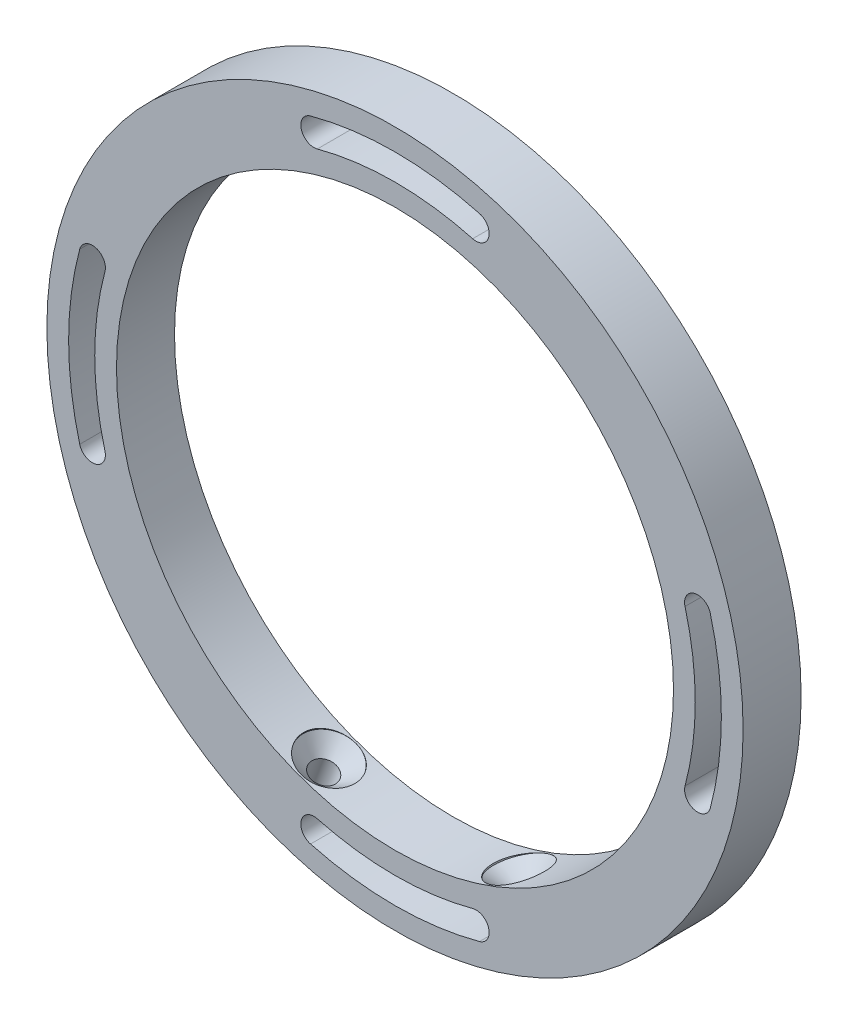
SolidWorks part; units mm, degrees
ref_plane "Piano frontale" through (0, 0, 0) normal (0, 0, 1) x (1, 0, 0)
ref_plane "Piano superiore" through (0, 0, 0) normal (0, 1, 0) x (1, 0, 0)
ref_plane "Piano destro" through (0, 0, 0) normal (1, 0, 0) x (0, 0, -1)
sketch "Schizzo2" plane through (0, 0, 0) normal (0, 0, 1) x (1, 0, 0)
  line L0 (0, -60) -> (0, 60) construction
  line L1 (-60, 0) -> (60, 0) construction
  line L2 (-15.5291, 57.9555) -> (0, 0) construction
  line L3 (0, 0) -> (13.9762, 52.16) construction
  line L4 (-52.16, 13.9762) -> (0, 0) construction
  line L5 (0, 0) -> (-52.16, -13.9762) construction
  line L6 (-13.9762, -52.16) -> (0, 0) construction
  line L7 (0, 0) -> (13.9762, -52.16) construction
  line L8 (52.16, -13.9762) -> (0, 0) construction
  line L9 (0, 0) -> (52.16, 13.9762) construction
  line L10 (13.3939, 49.9867) -> (14.5586, 54.3333) construction
  line L11 (-52.16, 13.9762) -> (-57.9555, 15.5291) construction
  line L12 (-52.16, -13.9762) -> (-57.9555, -15.5291) construction
  line L13 (-13.9762, -52.16) -> (-15.5291, -57.9555) construction
  line L14 (13.9762, -52.16) -> (15.5291, -57.9555) construction
  line L15 (52.16, 13.9762) -> (57.9555, 15.5291) construction
  circle A0 centre (0, 0) radius 60
  circle A1 centre (0, 0) radius 48
  arc A14 (-54.3333, 14.5586) -> (-54.3333, -14.5586) centre (0, 0) ccw
  arc A17 (-49.9867, 13.3939) -> (-49.9867, -13.3939) centre (0, 0) ccw
  arc A20 (-13.3939, -49.9867) -> (-14.5586, -54.3333) centre (-13.9762, -52.16) ccw
  arc A22 (14.5586, -54.3333) -> (13.3939, -49.9867) centre (13.9762, -52.16) ccw
  arc A23 (-54.3333, -14.5586) -> (-49.9867, -13.3939) centre (-52.16, -13.9762) ccw
  arc A24 (-49.9867, 13.3939) -> (-54.3333, 14.5586) centre (-52.16, 13.9762) ccw
  arc A25 (13.3939, 49.9867) -> (14.5586, 54.3333) centre (13.9762, 52.16) ccw
  arc A27 (54.3333, 14.5586) -> (49.9867, 13.3939) centre (52.16, 13.9762) ccw
  arc A28 (49.9867, -13.3939) -> (54.3333, -14.5586) centre (52.16, -13.9762) ccw
  arc A29 (-51.5325, 16.137) -> (-51.5325, -16.137) centre (0, 0) ccw construction
  arc A30 (14.5586, 54.3333) -> (-14.5586, 54.3333) centre (0, 0) ccw
  arc A31 (16.137, 51.5325) -> (-39.7413, 36.56) centre (0, 0) ccw construction
  arc A32 (13.3939, 49.9867) -> (-13.3939, 49.9867) centre (0, 0) ccw
  arc A33 (49.9867, -13.3939) -> (49.9867, 13.3939) centre (0, 0) ccw
  arc A34 (51.5325, -16.137) -> (51.5325, 16.137) centre (0, 0) ccw construction
  arc A35 (54.3333, -14.5586) -> (54.3333, 14.5586) centre (0, 0) ccw
  arc A36 (-13.3939, -49.9867) -> (13.3939, -49.9867) centre (0, 0) ccw
  arc A37 (-16.137, -51.5325) -> (16.137, -51.5325) centre (0, 0) ccw construction
  arc A38 (-14.5586, -54.3333) -> (14.5586, -54.3333) centre (0, 0) ccw
  arc A39 (-14.5586, 54.3333) -> (-13.3939, 49.9867) centre (-13.9762, 52.16) ccw
  dimension "D1" = 120
  dimension "D2" = 12
  dimension "D3" = 4.5
  dimension "D4" = 3.75
  dimension "D13" = 2.25
  dimension "D5" = 15
  dimension "D6" = 15
  dimension "D7" = 15
  dimension "D8" = 15
  dimension "D9" = 15
  dimension "D10" = 15
  dimension "D11" = 15
  dimension "D12" = 15
extrude "Estrusione-Estrusione1" add sketch "Schizzo2" along normal blind 10
hole_wizard "Foro svasato per Vite M4-1" positions "Schizzo3D4" profile "Schizzo4" countersink size "M4" standard "ISO"
sketch3d "Schizzo3D4"
  line L9 (0, 0, 0) -> (0, 0, 5) construction
  line L11 (16.417, -45.1052, 5) -> (0, 0, 5) construction
  line L12 (0, 0, 5) -> (-16.417, -45.1052, 5) construction
  line L14 (0, 0, 5) -> (0, -45.1052, 5) construction
  line L16 (16.417, -45.1052, 5) -> (-16.417, -45.1052, 5) construction
  point P0 (-16.417, -45.1052, 5)
  point P2 (16.417, -45.1052, 5)
  point P49 (0, -44.4681, 6.5)
  point P50 (-16.4272, -45.1015, 6.5)
  point P51 (0, 0, 0)
  point P53 (0, -44.5397, 6.5)
  point P54 (0, -45.1052, 5)
  point P55 (0, -44.3436, 6.5)
  point P56 (16.1383, -45.2057, 9.7052)
  dimension "D1" = 5
  dimension "D2" = 20
sketch "Schizzo4" plane through (-16.417, -45.1052, 5) normal (0, 0, 1) x (-0.9397, 0.342, 0)
  line L0 (0, 0) -> (0, 28.9028)
  line L1 (0, 28.9028) -> (2.15, 28.9028)
  line L2 (2.15, 28.9028) -> (2.15, 2.55)
  line L3 (2.15, 2.55) -> (4.7, 0)
  line L5 (4.7, 0) -> (0, 0)
  line L6 (-2.15, 2.55) -> (-4.7, 0) construction
  line L11 (0, -6.35) -> (0, 107.95) construction
  dimension "Thru Hole Dia." = 4.3
  dimension "Thru Hole Depth" = 28.9028
  dimension "Near C'Sink Dia." = 9.4
  dimension "Near C'Sink Angle" = 90
